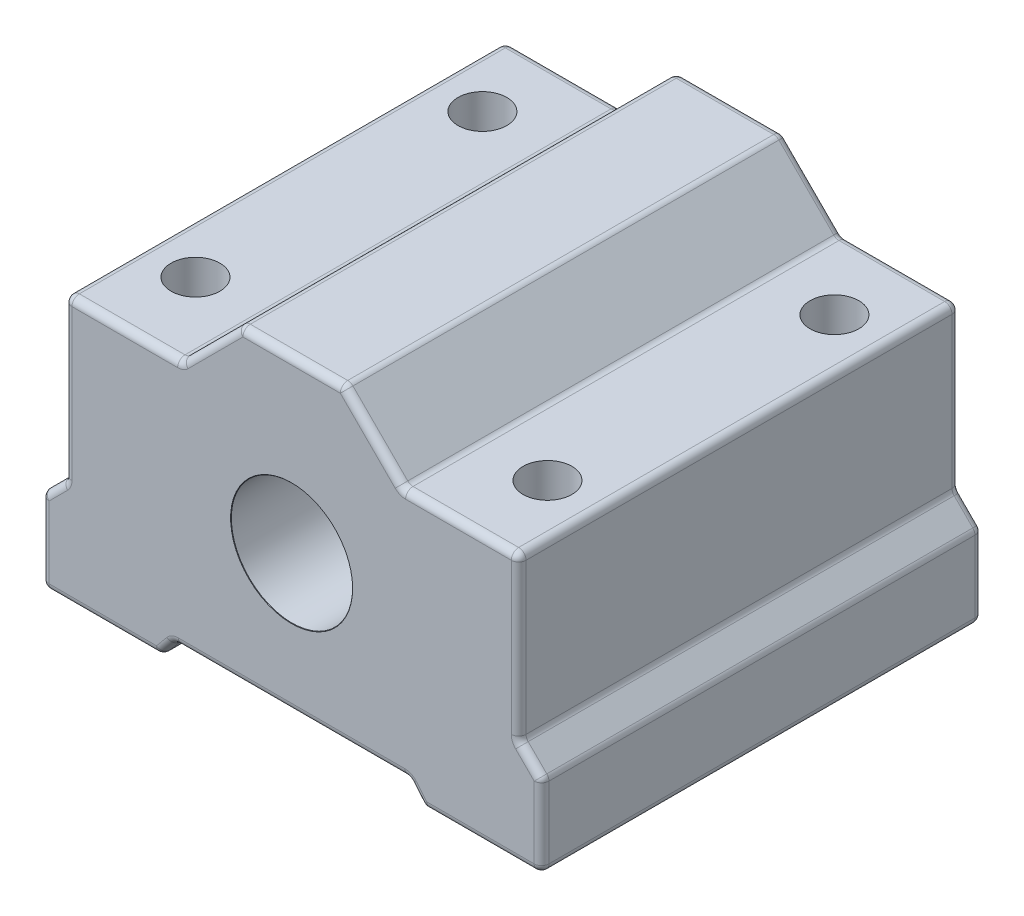
SolidWorks part; units mm, degrees
ref_plane "Front Plane" through (0, 0, 0) normal (0, 0, 1) x (1, 0, 0)
ref_plane "Top Plane" through (0, 0, 0) normal (0, 1, 0) x (1, 0, 0)
ref_plane "Right Plane" through (0, 0, 0) normal (1, 0, 0) x (0, 0, -1)
sketch "Sketch1" plane through (0, 0, 0) normal (0, 0, 1) x (1, 0, 0)
  line L0 (0, 0) -> (0, 1.5666) construction
  line L1 (-3.5, 4) -> (3.5, 4)
  line L2 (3.5, 4) -> (7.5, 0)
  line L3 (7.5, 0) -> (15.35, 0)
  line L4 (15.35, 0) -> (15.35, -10.9)
  line L5 (15.35, -10.9) -> (16.9, -12.45)
  line L6 (16.9, -12.45) -> (16.9, -18)
  line L7 (16.9, -18) -> (8.9, -18)
  line L8 (8.9, -18) -> (7.9, -16.8)
  line L9 (7.9, -16.8) -> (-7.9, -16.8)
  line L10 (-8.9, -18) -> (-7.9, -16.8)
  line L11 (-16.9, -18) -> (-8.9, -18)
  line L12 (-16.9, -12.45) -> (-16.9, -18)
  line L13 (-15.35, -10.9) -> (-16.9, -12.45)
  line L14 (-15.35, 0) -> (-15.35, -10.9)
  line L15 (-7.5, 0) -> (-15.35, 0)
  line L16 (-3.5, 4) -> (-7.5, 0)
  point P5 (0, 0)
  point P14 (1.5685, 2.0647)
  point P16 (1.75, 2.5855)
  point P17 (0, 0)
  point P18 (0, 0)
  point P19 (0, 0)
  point P20 (0.6981, -1.1183)
  point P21 (16.9, -12.7396)
  point P23 (0, -16.8)
  point P30 (0, 4)
  dimension "D1" = 7
  dimension "D2" = 15
  dimension "D3" = 30.7
  dimension "D4" = 33.8
  dimension "D5" = 15.8
  dimension "D6" = 8
  dimension "D7" = 18
  dimension "D8" = 20.8
  dimension "D9" = 4
  dimension "D10" = 10.9
  dimension "D11" = 4
extrude "Boss-Extrude1" add sketch "Sketch1" along normal blind 29.8
fillet "Fillet1" radius 0.5 48 edges at (3.5, 4, 14.9) (-3.5, 4, 14.9) (-7.5, 0, 14.9) (-15.35, 0, 14.9) (-15.35, -10.9, 14.9) (-16.9, -12.45, 14.9) (-16.9, -18, 14.9) (-8.9, -18, 14.9) (-7.9, -16.8, 14.9) (7.9, -16.8, 14.9) (8.9, -18, 14.9) (16.9, -18, 14.9) (16.9, -12.45, 14.9) (15.35, -10.9, 14.9) (15.35, 0, 14.9) (7.5, 0, 14.9) (11.425, 0, 29.8) (15.35, -5.45, 29.8) (16.125, -11.675, 29.8) (16.9, -15.225, 29.8) (12.9, -18, 29.8) (8.4, -17.4, 29.8) (0, -16.8, 29.8) (-8.4, -17.4, 29.8) (-12.9, -18, 29.8) (-16.9, -15.225, 29.8) (-16.125, -11.675, 29.8) (-15.35, -5.45, 29.8) (-11.425, 0, 29.8) (-5.5, 2, 29.8) (0, 4, 29.8) (5.5, 2, 29.8) (11.425, 0, 0) (15.35, -5.45, 0) (16.125, -11.675, 0) (16.9, -15.225, 0) (12.9, -18, 0) (8.4, -17.4, 0) (0, -16.8, 0) (-8.4, -17.4, 0) (-12.9, -18, 0) (-16.9, -15.225, 0) (-16.125, -11.675, 0) (-15.35, -5.45, 0) (-11.425, 0, 0) (-5.5, 2, 0) (0, 4, 0) (5.5, 2, 0)
hole_wizard "Ø8.2 (8.2) Diameter Hole1" positions "3DSketch1" profile "Sketch3" hole size "Ø8.2" standard "AS" end condition through all
sketch3d "3DSketch1"
  line L0 (7.6658, -16.8, 29.3) -> (-7.6658, -16.8, 29.3) construction
  line L1 (0, 0, 29.8) -> (0, 2.2986, 29.8) construction
  point P0 (0, -7.5135, 29.8)
  point P9 (0, 0, 0)
  point P10 (0, 0, 0)
  point P11 (0, 0, 0)
  dimension "D1" = 9.3
sketch "Sketch3" plane through (0, -7.5135, 29.8) normal (1, 0, 0) x (0, -1, 0)
  line L0 (0, 0) -> (0, 29.8)
  line L1 (0, 29.8) -> (4.1, 29.8)
  line L2 (4.1, 29.8) -> (4.1, 0.025)
  line L3 (4.1, 0.025) -> (4.125, 0)
  line L5 (4.125, 0) -> (0, 0)
  line L6 (-4.1, 0.025) -> (-4.125, 0) construction
  line L11 (0, -6.35) -> (0, 107.95) construction
  dimension "Thru Hole Dia." = 8.2
  dimension "Thru Hole Depth" = 29.8
  dimension "Near C'Sink Dia." = 8.25
  dimension "Near C'Sink Angle" = 90
hole_wizard "M4 Tapped Hole1" positions "3DSketch2" profile "Sketch4" tap size "M4" standard "AS" end condition through all
sketch3d "3DSketch2"
  point P0 (11.9, -18, 24.4)
  point P2 (11.9, -18, 5)
  point P4 (-11.9, -18, 5)
  point P6 (-11.9, -18, 24.4)
  point P9 (0, 0, 0)
  point P10 (0, 0, 0)
  dimension "D1" = 5
  dimension "D2" = 5
  dimension "D3" = 5
  dimension "D4" = 5
  dimension "D5" = 5.4
  dimension "D6" = 5
sketch "Sketch4" plane through (11.9, -18, 24.4) normal (1, 0, 0) x (0, 0, -1)
  line L0 (0, 0) -> (0, 22)
  line L1 (0, 22) -> (1.65, 22)
  line L2 (1.65, 22) -> (1.65, 0.375)
  line L3 (1.65, 0.375) -> (2.025, 0)
  line L5 (2.025, 0) -> (0, 0)
  line L6 (-1.65, 0.375) -> (-2.025, 0) construction
  line L11 (0, -6.35) -> (0, 107.95) construction
  dimension "Thru Tap Drill Dia." = 3.3
  dimension "Thru Tap Drill Depth" = 22
  dimension "Near C'Sink Dia." = 4.05
  dimension "Near C'Sink Angle" = 90
cosmetic thread "Hole Thread1" parameters "D2"=4
cosmetic thread "Hole Thread2" parameters "D2"=4
cosmetic thread "Hole Thread3" parameters "D2"=4
cosmetic thread "Hole Thread4" parameters "D2"=4
